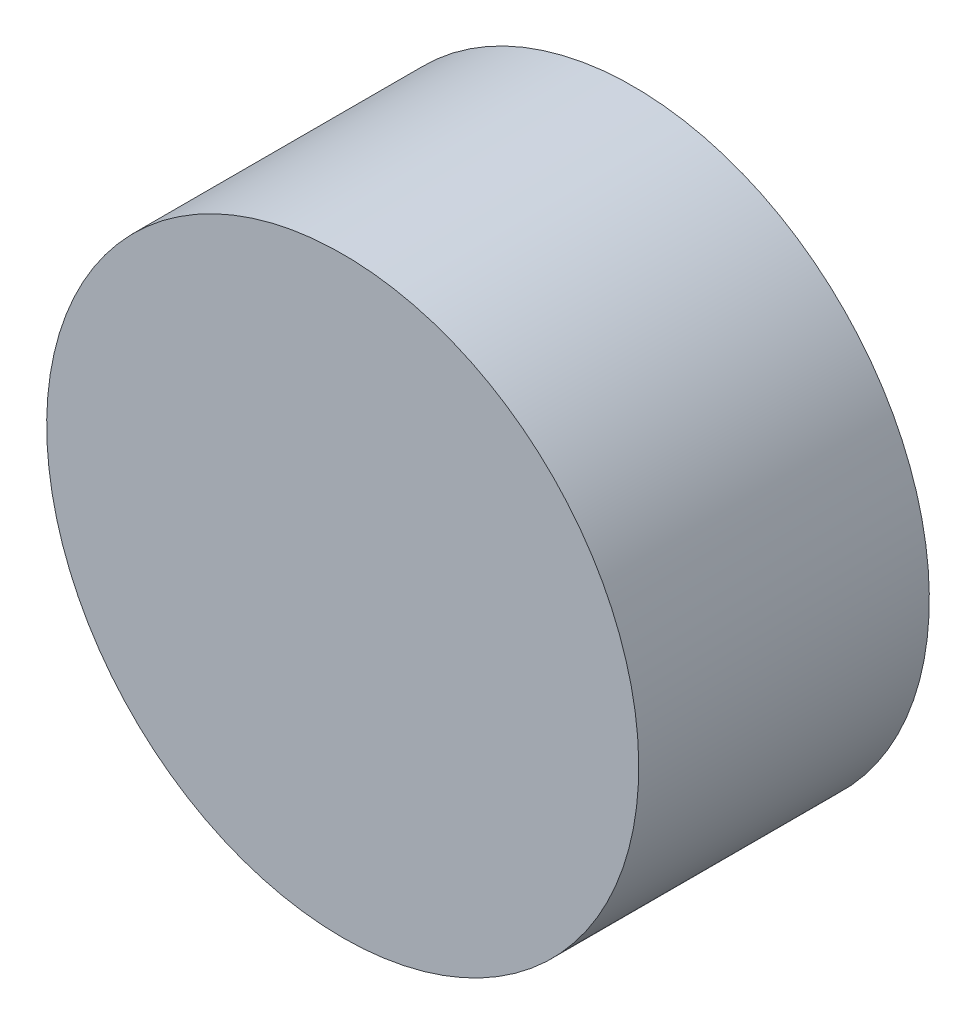
SolidWorks part; units mm, degrees
ref_plane "Front Plane" through (0, 0, 0) normal (1, 0, 0) x (0, 1, 0)
ref_plane "Top Plane" through (0, 0, 0) normal (0, 0, 1) x (0, 1, 0)
ref_plane "Right Plane" through (0, 0, 0) normal (0, 1, 0) x (-1, 0, 0)
sketch "Sketch1" plane through (0, 0, 0) normal (1, 0, 0) x (0, 1, 0)
  line L1 (-32.8263, 0) -> (0, 0)
  line L2 (-32.8263, 0) -> (-32.8263, -32.2212)
  line L3 (-32.8263, -32.2212) -> (0, -32.2212)
  line L4 (0, 0) -> (0, -32.2212)
  line L5 (-32.8263, 0) -> (0, -32.2212) construction
  line L6 (-32.8263, -32.2212) -> (0, 0) construction
  point P0 (-16.4131, -16.1106)
  point P5 (0, 0)
  point P6 (0, -1.4716)
  point P7 (-30.6721, 31.679)
  point P8 (0, 0)
  dimension "D1" = 45.9975
  dimension "D2" = 44.467
revolve "Revolve1" add sketch "Sketch1" angle 360 about L4
